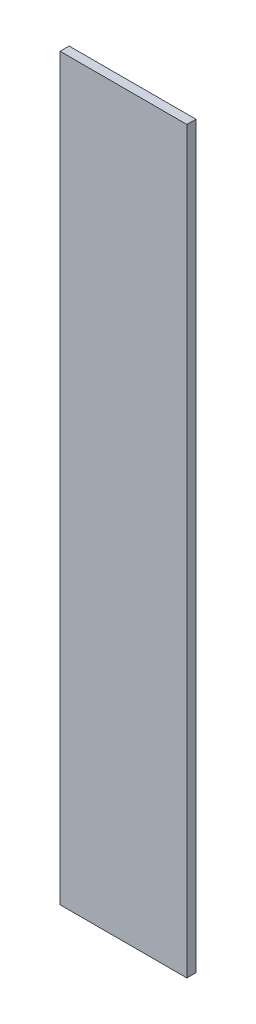
SolidWorks part; units mm, degrees
ref_plane "Front Plane" through (0, 0, 0) normal (1, 0, 0) x (0, 1, 0)
ref_plane "Top Plane" through (0, 0, 0) normal (0, 0, 1) x (0, 1, 0)
ref_plane "Right Plane" through (0, 0, 0) normal (0, 1, 0) x (-1, 0, 0)
sketch "Sketch2" plane through (0, 0, 0) normal (0, 0, 1) x (0, 1, 0)
  line L1 (0, 0) -> (518.16, 0)
  line L2 (0, 0) -> (0, 88.9)
  line L3 (0, 88.9) -> (518.16, 88.9)
  line L4 (518.16, 0) -> (518.16, 88.9)
  dimension "D1" = 88.9
  dimension "D2" = 518.16
extrude "Boss-Extrude1" add sketch "Sketch2" along normal blind 6.35
